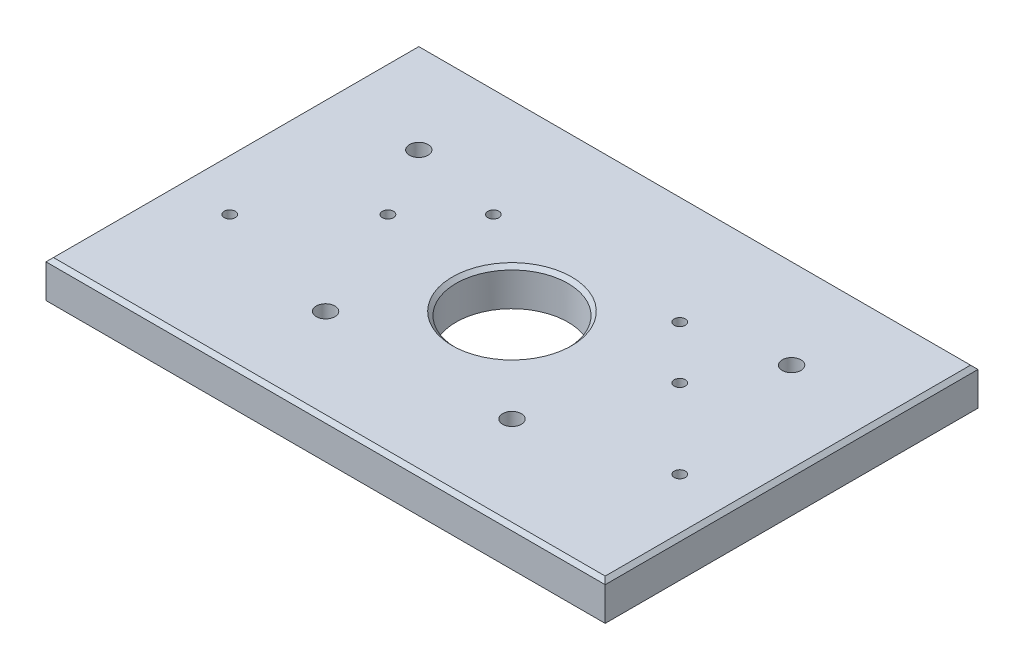
SolidWorks part; units mm, degrees
ref_plane "Front Plane" through (0, 0, 0) normal (0, 0, 1) x (1, 0, 0)
ref_plane "Top Plane" through (0, 0, 0) normal (0, 1, 0) x (1, 0, 0)
ref_plane "Right Plane" through (0, 0, 0) normal (1, 0, 0) x (0, 0, -1)
sketch "Sketch1" plane through (0, 0, 0) normal (0, 1, 0) x (1, 0, 0)
  line L1 (0, 0) -> (150, 0)
  line L2 (0, 0) -> (0, 100)
  line L3 (0, 100) -> (150, 100)
  line L4 (150, 0) -> (150, 100)
  dimension "D1" = 100
  dimension "D2" = 150
extrude "Boss-Extrude1" add sketch "Sketch1" along normal blind 10
sketch "Sketch2" plane through (0, 10, 0) normal (0, 1, 0) x (1, 0, 0)
  line L0 (0, 100) -> (0, 0) construction
  line L1 (150, 100) -> (0, 100) construction
  line L2 (50, 70) -> (0, 20) construction
  line L3 (35.8579, 55.8579) -> (14.6447, 34.6447) construction
  line L4 (75, 100) -> (75, 0) construction
  line L5 (0, 0) -> (150, 0) construction
  line L6 (100, 70) -> (150, 20) construction
  circle A0 centre (50, 70) radius 1.5
  circle A1 centre (35.8579, 55.8579) radius 1.5
  circle A2 centre (14.6447, 34.6447) radius 1.5
  circle A3 centre (75, 50) radius 15
  circle A4 centre (50, 25) radius 2.5
  circle A5 centre (25, 75) radius 2.5
  circle A6 centre (125, 75) radius 2.5
  circle A7 centre (100, 25) radius 2.5
  circle A8 centre (135.3553, 34.6447) radius 1.5
  circle A9 centre (114.1421, 55.8579) radius 1.5
  circle A10 centre (100, 70) radius 1.5
  dimension "D1" = 3
  dimension "D7" = 30
  dimension "D9" = 25
  dimension "D11" = 5
  dimension "D2" = 50
  dimension "D3" = 30
  dimension "D4" = 45
  dimension "D5" = 20
  dimension "D6" = 30
  dimension "D10" = 25
  dimension "D12" = 25
  dimension "D13" = 25
extrude "Cut-Extrude1" cut sketch "Sketch2" against normal through all contours A3 | A10 | A6 | A9 | A8 | A7 | A4 | A2 | A1 | A0 | A5
chamfer "Chamfer1" distance 1 angle 45 5 edges at (75, 10, -35) (150, 10, -50) (75, 10, -100) (0, 10, -50) (75, 10, 0)
